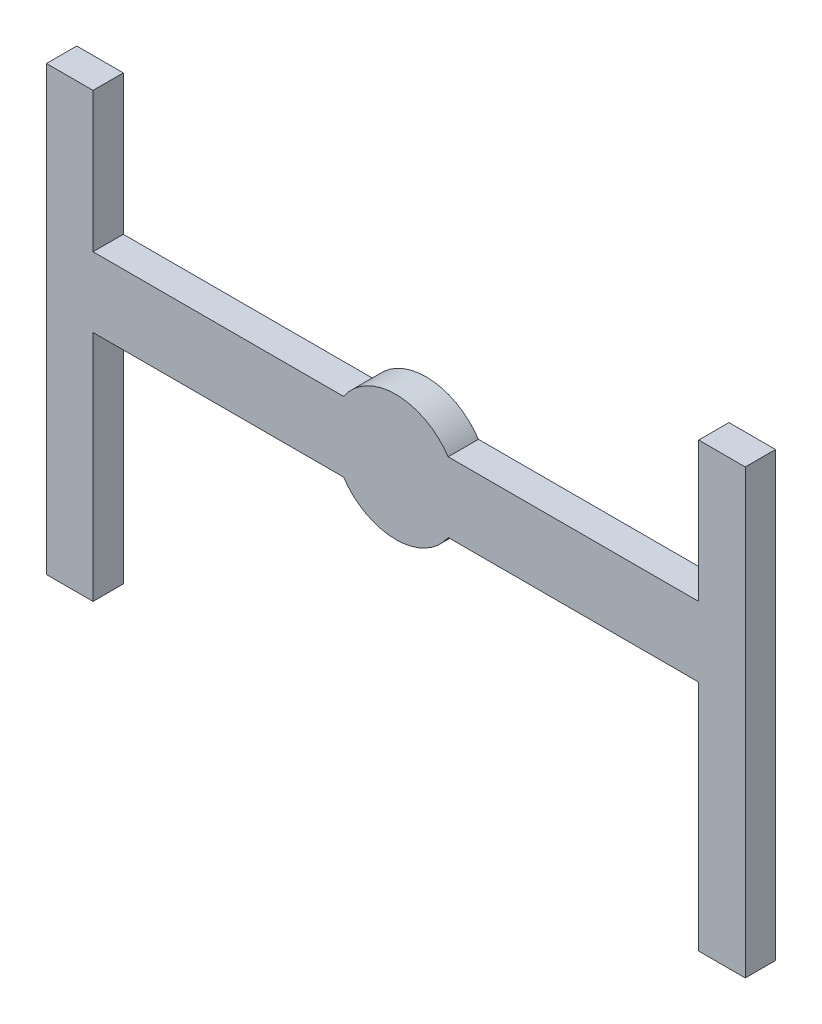
SolidWorks part; units mm, degrees
ref_plane "Plan de face" through (0, 0, 0) normal (0, 0, 1) x (1, 0, 0)
ref_plane "Plan de dessus" through (0, 0, 0) normal (0, 1, 0) x (1, 0, 0)
ref_plane "Plan de droite" through (0, 0, 0) normal (1, 0, 0) x (0, 0, -1)
sketch "Esquisse1" plane through (0, 0, 0) normal (0, 0, 1) x (1, 0, 0)
  line L1 (0, 0) -> (3000, 0)
  line L2 (0, 0) -> (0, 1900)
  line L3 (0, 1900) -> (3000, 1900)
  line L4 (3000, 0) -> (3000, 1900)
  dimension "D1" = 3000
  dimension "D2" = 1900
extrude "Boss.-Extru.1" add sketch "Esquisse1" against normal blind 130 contours L3 L4 L1 L2
sketch "Esquisse3" plane through (0, 0, 0) normal (0, 0, 1) x (1, 0, 0)
  line L0 (200, 1900) -> (200, 1300)
  line L1 (0, 1900) -> (3000, 1900) construction
  line L2 (200, 1300) -> (2800, 1300)
  line L3 (2800, 1300) -> (2800, 1900)
  line L4 (200, 1900) -> (2800, 1900)
  line L5 (0, 0) -> (0, 1900) construction
  line L6 (3000, 0) -> (3000, 1900) construction
  line L7 (200, 0) -> (200, 1000)
  line L8 (0, 0) -> (3000, 0) construction
  line L9 (200, 1000) -> (2800, 1000)
  line L10 (2800, 1000) -> (2800, 0)
  line L11 (200, 0) -> (2800, 0)
  dimension "D1" = 200
  dimension "D2" = 200
  dimension "D3" = 300
  dimension "D4" = 600
sketch "Esquisse4" plane through (0, 0, 0) normal (0, 0, 1) x (1, 0, 0)
  line L0 (200, 1900) -> (2800, 1900) construction
  line L1 (0, 0) -> (0, 1900) construction
  line L2 (200, 0) -> (200, 1000) construction
  line L3 (200, 0) -> (2800, 0) construction
  line L4 (2800, 1000) -> (2800, 0) construction
  line L5 (200, 1000) -> (2800, 1000) construction
  line L6 (200, 1900) -> (200, 1300) construction
  line L7 (2800, 1300) -> (2800, 1900) construction
  line L8 (200, 1300) -> (2800, 1300) construction
  line L9 (200, 0) -> (200, 1000)
  line L10 (200, 0) -> (2800, 0)
  line L11 (2800, 1000) -> (2800, 0)
  line L12 (200, 1000) -> (1275.5006, 1000)
  line L13 (200, 1900) -> (200, 1300)
  line L14 (200, 1900) -> (2800, 1900)
  line L15 (2800, 1300) -> (2800, 1900)
  line L16 (200, 1300) -> (1275.5006, 1300)
  line L17 (1724.4994, 1300) -> (2800, 1300)
  line L18 (1724.4994, 1000) -> (2800, 1000)
  circle A1 centre (1500, 1150) radius 270
  line M3 (0, 0) -> (3000, 0)
  line M5 (3000, 1900) -> (0, 1900)
  dimension "D4" = 540
  dimension "D1" = 750
  dimension "D2" = 1500
extrude "Enlèv. mat.-Extru.1" cut sketch "Esquisse4" against normal blind 130 contours A1 L17 L15 L13 L16 M5 | A1 L12 L9 L11 L18 M3
